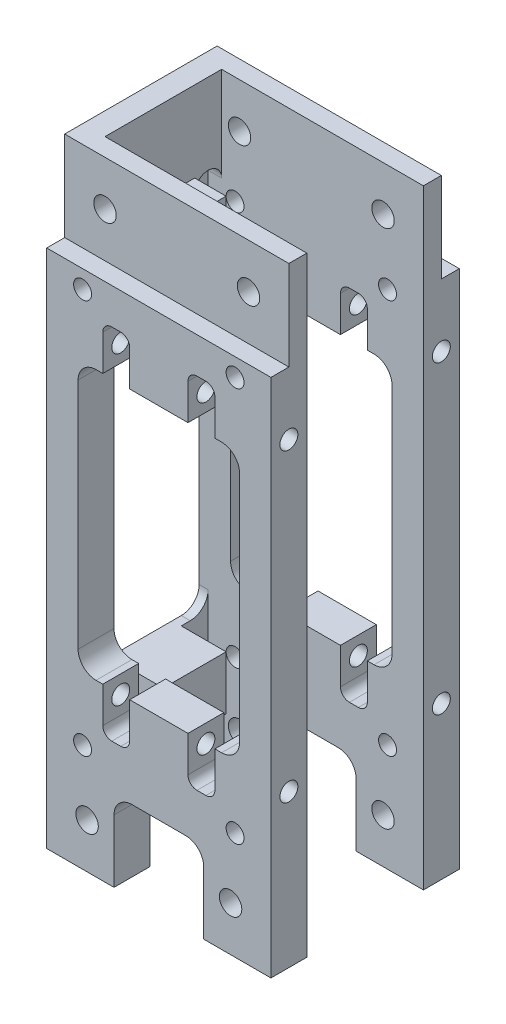
SolidWorks part; units mm, degrees
material "6061-T6 (SS)"
ref_plane "前视基准面" through (0, 0, 0) normal (0, 0, 1) x (1, 0, 0)
ref_plane "上视基准面" through (0, 0, 0) normal (0, 1, 0) x (1, 0, 0)
ref_plane "右视基准面" through (0, 0, 0) normal (1, 0, 0) x (0, 0, -1)
sketch "草图1" plane through (0, 0, 0) normal (0, 1, 0) x (1, 0, 0)
  line L1 (-6, -6) -> (6, -6) construction
  line L2 (-6, -6) -> (-6, 6) construction
  line L3 (-6, 6) -> (6, 6) construction
  line L4 (6, -6) -> (6, 6) construction
  line L5 (0, 6) -> (0, -6) construction
  line L6 (-6, 0) -> (6, 0) construction
  line L10 (11.5, -6.5) -> (6, -6.5)
  line L11 (-12.5, 10.5) -> (12.5, 10.5)
  line L12 (-12.5, 10.5) -> (-12.5, -10.5)
  line L13 (-12.5, -10.5) -> (12.5, -10.5)
  line L14 (12.5, 10.5) -> (12.5, -10.5)
  line L15 (0, -10.5) -> (0, 10.5) construction
  line L16 (-12.5, 0) -> (12.5, 0) construction
  line L17 (-11.5, -3.5) -> (-6, -3.5)
  line L18 (-11.5, -3.5) -> (-11.5, -6.5)
  line L19 (-11.5, -6.5) -> (-6, -6.5)
  line L20 (-6, -3.5) -> (-6, -6.5)
  line L21 (-8.75, -6.5) -> (-8.75, -3.5) construction
  line L22 (-11.5, -5) -> (-6, -5) construction
  line L27 (0, -6) -> (0, 6) construction
  line L29 (6, -3.5) -> (6, -6.5)
  line L30 (11.5, -3.5) -> (6, -3.5)
  line L31 (11.5, -3.5) -> (11.5, -6.5)
  line L32 (11.5, 3.5) -> (11.5, 6.5)
  line L33 (11.5, 3.5) -> (6, 3.5)
  line L34 (6, 3.5) -> (6, 6.5)
  line L35 (11.5, 6.5) -> (6, 6.5)
  line L36 (-11.5, 6.5) -> (-6, 6.5)
  line L37 (-6, 3.5) -> (-6, 6.5)
  line L38 (-11.5, 3.5) -> (-6, 3.5)
  line L39 (-11.5, 3.5) -> (-11.5, 6.5)
  line L40 (8.75, -6.5) -> (8.75, -3.5) construction
  line L41 (-6.5, 6.5) -> (6.5, 6.5)
  line L42 (-6.5, 6.5) -> (-6.5, -6.5)
  line L43 (-6.5, -6.5) -> (6.5, -6.5)
  line L44 (6.5, 6.5) -> (6.5, -6.5)
  line L45 (0, -6.5) -> (0, 6.5) construction
  line L46 (-6.5, 0) -> (6.5, 0) construction
  point P0 (0, 0)
  point P4 (0, 0)
  point P12 (0, 0)
  point P13 (0, 0)
  point P195 (-8.75, -5)
  dimension "D1" = 12
  dimension "D2" = 21
  dimension "D3" = 25
  dimension "D4" = 5.5
  dimension "D5" = 5.5
  dimension "D6" = 3
  dimension "D7" = 13
  dimension "D8" = 13
  dimension "D9" = 5.5
extrude "凸台-拉伸2" add sketch "草图1" along normal mid plane 68
sketch "草图2" plane through (0, 0, -10.5) normal (0, 0, -1) x (-1, 0, 0)
  line L0 (0, -34) -> (0, 34) construction
  line L1 (12.5, -34) -> (-12.5, -34) construction
  line L2 (12.5, 34) -> (-12.5, 34) construction
  line L3 (5, 25) -> (-5, 25) construction
  line L4 (9, 15) -> (-9, 15)
  line L5 (9, 15) -> (9, -15)
  line L6 (9, -15) -> (-9, -15)
  line L7 (-9, 15) -> (-9, -15)
  line L8 (0, -15) -> (0, 15) construction
  line L9 (9, 0) -> (-9, 0) construction
  line L10 (5, -34) -> (-5, -34)
  line L11 (5, -34) -> (5, -25)
  line L12 (5, -25) -> (-5, -25)
  line L13 (-5, -34) -> (-5, -25)
  line L14 (0, -25) -> (0, -34) construction
  line L15 (5, -29.5) -> (-5, -29.5) construction
  line L20 (-5, 34) -> (-5, 25) construction
  line L21 (5, 34) -> (-5, 34) construction
  line L22 (5, 34) -> (5, 25) construction
  line L23 (-3.25, -20) -> (-6.25, -20)
  line L30 (3.25, -15) -> (6.25, -15)
  line L31 (3.25, -15) -> (3.25, -20)
  line L32 (3.25, -20) -> (6.25, -20)
  line L33 (6.25, -15) -> (6.25, -20)
  line L34 (4.75, -20) -> (4.75, -15) construction
  line L35 (3.25, -17.5) -> (6.25, -17.5) construction
  line L36 (-6.25, -15) -> (-6.25, -20)
  line L37 (-3.25, -15) -> (-6.25, -15)
  line L38 (-3.25, -15) -> (-3.25, -20)
  line L39 (3.25, 20) -> (6.25, 20)
  line L40 (6.25, 15) -> (6.25, 20)
  line L41 (3.25, 15) -> (6.25, 15)
  line L42 (3.25, 15) -> (3.25, 20)
  line L43 (-3.25, 15) -> (-3.25, 20)
  line L44 (-3.25, 15) -> (-6.25, 15)
  line L45 (-6.25, 15) -> (-6.25, 20)
  line L46 (-3.25, 20) -> (-6.25, 20)
  circle A0 centre (8.5, -22) radius 1
  circle A1 centre (-8.5, -22) radius 1
  circle A2 centre (-8.5, 22) radius 1
  circle A3 centre (8.5, 22) radius 1
  point P6 (0, 0)
  point P158 (0, -29.5)
  point P186 (4.75, -17.5)
  dimension "D4" = 2
  dimension "D1" = 18
  dimension "D2" = 30
  dimension "D3" = 10
  dimension "D5" = 17
  dimension "D6" = 10
  dimension "D7" = 2
  dimension "D8" = 3
  dimension "D9" = 5
  dimension "D10" = 12.5
extrude "切除-拉伸4" cut sketch "草图2" against normal blind 60
sketch "草图3" plane through (12.5, 0, 0) normal (1, 0, 0) x (0, 0, -1)
  line L1 (6.5, 19) -> (-6.5, 19)
  line L2 (6.5, 19) -> (6.5, -19)
  line L3 (6.5, -19) -> (-6.5, -19)
  line L4 (-6.5, 19) -> (-6.5, -19)
  line L5 (0, -19) -> (0, 19) construction
  line L6 (6.5, 0) -> (-6.5, 0) construction
  line L12 (10.5, -15) -> (6.5, -15)
  line L13 (10.5, -20) -> (10.5, -15)
  line L14 (6.5, -20) -> (10.5, -20)
  line L15 (6.5, -15) -> (6.5, -20)
  line L16 (10.5, -15) -> (6.5, -15) construction
  line L17 (10.5, -20) -> (10.5, -15) construction
  line L18 (6.5, -20) -> (10.5, -20) construction
  line L19 (6.5, -15) -> (6.5, -20) construction
  circle A0 centre (8.5, -17) radius 1
  circle A1 centre (8.5, 17) radius 1
  circle A2 centre (-8.5, 17) radius 1
  circle A3 centre (-8.5, -17) radius 1
  point P0 (0, 0)
  dimension "D4" = 2
  dimension "D5" = 0
  dimension "D1" = 13
  dimension "D2" = 4
  dimension "D3" = 17
  dimension "D6" = 2
extrude "切除-拉伸2" cut sketch "草图3" against normal through all
sketch "草图6" plane through (0, -34, 0) normal (0, -1, 0) x (1, 0, 0)
  line L0 (11.5, 3.5) -> (6.5, 3.5) construction
  line L1 (6.5, -3.5) -> (10, -3.5)
  line L2 (6.5, -3.5) -> (6.5, 3.5)
  line L3 (6.5, 3.5) -> (10, 3.5)
  line L4 (10, -3.5) -> (10, 3.5)
  line L5 (8.25, 3.5) -> (8.25, -3.5) construction
  line L6 (6.5, 0) -> (10, 0) construction
  line L7 (0, 0) -> (0, -6.5) construction
  line L8 (-5, -6.5) -> (5, -6.5) construction
  line L9 (-6.5, 3.5) -> (-10, 3.5)
  line L10 (-10, -3.5) -> (-10, 3.5)
  line L11 (-6.5, -3.5) -> (-10, -3.5)
  line L12 (-6.5, -3.5) -> (-6.5, 3.5)
  line L13 (-12.5, -10.5) -> (-12.5, 10.5) construction
  point P192 (8.25, 0)
  dimension "D1" = 2.5
extrude "切除-拉伸5" cut sketch "草图6" against normal offset from surface (9 mm away) 6 up to face at (10.5, -19, 0)
sketch "草图11" plane through (0, 34, 0) normal (0, 1, 0) x (1, 0, 0)
  line L0 (-6.5, 3.5) -> (-6.5, -3.5) construction
  line L1 (-6.5, -3.5) -> (-10, -3.5) construction
  line L2 (-10, -3.5) -> (-10, 3.5) construction
  line L3 (-10, 3.5) -> (-6.5, 3.5) construction
  line L4 (6.5, -3.5) -> (6.5, 3.5) construction
  line L5 (6.5, 3.5) -> (10, 3.5) construction
  line L6 (10, 3.5) -> (10, -3.5) construction
  line L7 (10, -3.5) -> (6.5, -3.5) construction
  line L8 (-6.5, 3.5) -> (-6.5, -3.5)
  line L9 (-6.5, -3.5) -> (-10, -3.5)
  line L10 (-10, -3.5) -> (-10, 3.5)
  line L11 (-10, 3.5) -> (-6.5, 3.5)
  line L12 (6.5, -3.5) -> (6.5, 3.5)
  line L13 (6.5, 3.5) -> (10, 3.5)
  line L14 (10, 3.5) -> (10, -3.5)
  line L15 (10, -3.5) -> (6.5, -3.5)
extrude "切除-拉伸9" cut sketch "草图11" against normal offset from surface (9 mm away) 6 up to face at (10.5, 19, 0)
sketch "草图7" plane through (0, 0, -10.5) normal (0, 0, -1) x (-1, 0, 0)
  line L0 (0, -25) -> (0, -30.2112) construction
  line L1 (5, -25) -> (-5, -25) construction
  line L2 (12.5, -34) -> (5, -34) construction
  line L3 (0, 0) -> (-12.5, 0) construction
  line L4 (-12.5, 34) -> (-12.5, -34) construction
  circle A0 centre (8, -29) radius 1.25
  circle A1 centre (-8, -29) radius 1.25
  circle A2 centre (-8, 29) radius 1.25
  circle A3 centre (8, 29) radius 1.25
  dimension "D2" = 2.5
  dimension "D3" = 5
  dimension "D1" = 16
extrude "切除-拉伸6" cut sketch "草图7" against normal through all
sketch "草图9" plane through (0, 0, -10.5) normal (0, 0, -1) x (-1, 0, 0)
  line L0 (-12.5, 34) -> (-12.5, -34) construction
  line L1 (12.5, 34) -> (-12.5, 34)
  line L2 (12.5, 34) -> (12.5, 24)
  line L3 (12.5, 24) -> (-12.5, 24)
  line L4 (-12.5, 34) -> (-12.5, 24)
  line L5 (0, 24) -> (0, 34) construction
  line L6 (12.5, 29) -> (-12.5, 29) construction
  point P272 (0, 29)
  dimension "D1" = 10
extrude "切除-拉伸7" cut sketch "草图9" against normal blind 2
sketch "草图10" plane through (0, 0, 10.5) normal (0, 0, 1) x (1, 0, 0)
  line L0 (-12.5, 34) -> (-12.5, -34) construction
  line L1 (12.5, 34) -> (-12.5, 34)
  line L2 (12.5, 34) -> (12.5, 24)
  line L3 (12.5, 24) -> (-12.5, 24)
  line L4 (-12.5, 34) -> (-12.5, 24)
  line L5 (0, 24) -> (0, 34) construction
  line L6 (12.5, 29) -> (-12.5, 29) construction
  line L7 (12.5, 24) -> (-12.5, 24) construction
  point P236 (0, 29)
extrude "切除-拉伸8" cut sketch "草图10" against normal blind 2
sketch "草图12" plane through (12.5, 0, 0) normal (1, 0, 0) x (0, 0, -1)
  line L0 (-6.5, 19) -> (-6.5, -19) construction
  line L1 (6.5, 34) -> (-6.5, 34)
  line L2 (6.5, 34) -> (6.5, -34)
  line L3 (6.5, -34) -> (-6.5, -34)
  line L4 (-6.5, 34) -> (-6.5, -34)
  line L5 (0, -34) -> (0, 34) construction
  line L6 (6.5, 0) -> (-6.5, 0) construction
  line L7 (-6.5, 19) -> (-6.5, -19) construction
  line L8 (10.5, -34) -> (-10.5, -34) construction
  point P0 (0, 0)
extrude "切除-拉伸10" cut sketch "草图12" against normal up to next
sketch "草图13" plane through (-11.5, 0, 0) normal (1, 0, 0) x (0, 0, -1)
  line L0 (0, -25) -> (0, -34) construction
  line L1 (-6.5, -34) -> (-3.5, -34)
  line L2 (-6.5, -34) -> (-6.5, -23.5)
  line L4 (-3.5, -34) -> (-3.5, -23.5)
  line L5 (-5, -23.5) -> (-5, -34) construction
  line L6 (-6.5, -28.75) -> (-3.5, -28.75) construction
  line L7 (3.5, -25) -> (-3.5, -25) construction
  line L8 (-3.5, -34) -> (3.5, -34) construction
  line L10 (3.5, -34) -> (3.5, -23.5)
  line L11 (6.5, -34) -> (3.5, -34)
  line L12 (6.5, -34) -> (6.5, -23.5)
  line L13 (0, 0) -> (10.5, 0) construction
  line L14 (10.5, 24) -> (10.5, -34) construction
  line L16 (-3.5, 34) -> (-3.5, 23.5)
  line L17 (-6.5, 34) -> (-3.5, 34)
  line L18 (-6.5, 34) -> (-6.5, 23.5)
  line L19 (6.5, 34) -> (6.5, 23.5)
  line L20 (6.5, 34) -> (3.5, 34)
  line L21 (3.5, 34) -> (3.5, 23.5)
  line L23 (6.5, 34) -> (6.5, 19) construction
  line L24 (-3.5, -19) -> (-3.5, -25) construction
  arc A4 (-6.5, -23.5) -> (-3.5, -23.5) centre (-5, -23.5) ccw
  arc A5 (6.5, -23.5) -> (3.5, -23.5) centre (5, -23.5) cw
  arc A6 (6.5, 23.5) -> (3.5, 23.5) centre (5, 23.5) ccw
  arc A7 (-3.5, 23.5) -> (-6.5, 23.5) centre (-5, 23.5) ccw
  point P172 (-5, -28.75)
extrude "凸台-拉伸4" add sketch "草图13" along normal up to surface (1.5 mm away) up to face at (-10, -29.5, 0)
fillet "R2" radius 2 16 edges at (5, -25, 8.5) (5, -25, -8.5) (-5, -25, 8.5) (-5, -25, -8.5) (9, -15, 8.5) (9, -15, -8.5) (9, 15, 8.5) (9, 15, -8.5) (-9, 15, 8.5) (-9, 15, -8.5) (-9, -15, 8.5) (-9, -15, -8.5) (-12, -19, 6.5) (-12, 19, -6.5) (-12, 19, 6.5) (-12, -19, -6.5)
fillet "R1" radius 1 16 edges at (6.25, 20, -8.5) (3.25, 20, -8.5) (-6.25, 20, -8.5) (-3.25, 20, -8.5) (3.25, 20, 8.5) (-6.25, 20, 8.5) (-3.25, 20, 8.5) (6.25, 20, 8.5) (6.25, -20, 8.5) (3.25, -20, 8.5) (-3.25, -20, 8.5) (-6.25, -20, 8.5) (3.25, -20, -8.5) (-6.25, -20, -8.5) (-3.25, -20, -8.5) (6.25, -20, -8.5)
